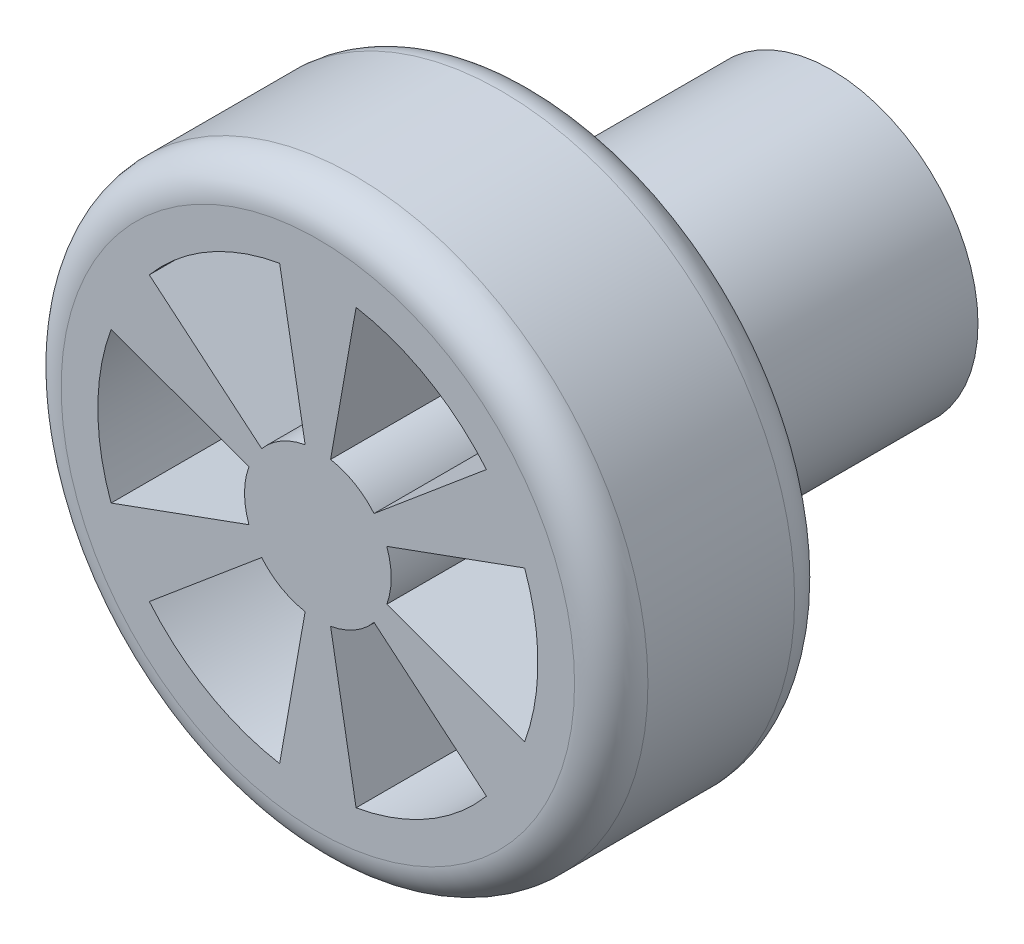
SolidWorks part; units mm, degrees
ref_plane "Front Plane" through (0, 0, 0) normal (0, 0, 1) x (1, 0, 0)
ref_plane "Top Plane" through (0, 0, 0) normal (0, 1, 0) x (1, 0, 0)
ref_plane "Right Plane" through (0, 0, 0) normal (1, 0, 0) x (0, 0, -1)
sketch "Sketch1" plane through (0, 0, 0) normal (0, 0, 1) x (1, 0, 0)
  circle A0 centre (0, 0) radius 101.6
extrude "Boss-Extrude2" add sketch "Sketch1" along normal blind 76.2
sketch "Sketch4" plane through (0, 0, 76.2) normal (0, 0, 1) x (1, 0, 0)
  circle A0 centre (0, 0) radius 25.4
sketch "Sketch5" plane through (0, 0, 0) normal (0, 0, -1) x (-1, 0, 0)
  line L0 (25.4, 0) -> (76.2, 0) construction
  line L1 (23.8682, 8.6873) -> (71.6046, 26.0619)
  line L2 (23.8682, -8.6873) -> (71.6046, -26.0619)
  line L3 (19.4575, -16.3268) -> (58.3726, -48.9804)
  line L4 (4.4107, -25.0141) -> (13.232, -75.0424)
  line L5 (-4.4107, -25.0141) -> (-13.232, -75.0424)
  line L6 (-19.4575, -16.3268) -> (-58.3726, -48.9804)
  line L7 (-23.8682, -8.6873) -> (-71.6046, -26.0619)
  line L8 (-23.8682, 8.6873) -> (-71.6046, 26.0619)
  line L9 (-19.4575, 16.3268) -> (-58.3726, 48.9804)
  line L10 (-4.4107, 25.0141) -> (-13.232, 75.0424)
  line L11 (4.4107, 25.0141) -> (13.232, 75.0424)
  line L12 (19.4575, 16.3268) -> (58.3726, 48.9804)
  arc A0 (71.6046, -26.0619) -> (71.6046, 26.0619) centre (0, 0) ccw
  arc A1 (23.8682, -8.6873) -> (23.8682, 8.6873) centre (0, 0) ccw
  arc A2 (13.232, -75.0424) -> (58.3726, -48.9804) centre (0, 0) ccw
  arc A3 (4.4107, -25.0141) -> (19.4575, -16.3268) centre (0, 0) ccw
  arc A4 (-58.3726, -48.9804) -> (-13.232, -75.0424) centre (0, 0) ccw
  arc A5 (-19.4575, -16.3268) -> (-4.4107, -25.0141) centre (0, 0) ccw
  arc A6 (-71.6046, 26.0619) -> (-71.6046, -26.0619) centre (0, 0) ccw
  arc A7 (-23.8682, 8.6873) -> (-23.8682, -8.6873) centre (0, 0) ccw
  arc A8 (-13.232, 75.0424) -> (-58.3726, 48.9804) centre (0, 0) ccw
  arc A9 (-4.4107, 25.0141) -> (-19.4575, 16.3268) centre (0, 0) ccw
  arc A10 (58.3726, 48.9804) -> (13.232, 75.0424) centre (0, 0) ccw
  arc A11 (19.4575, 16.3268) -> (4.4107, 25.0141) centre (0, 0) ccw
  point P31 (0, 0)
  dimension "D1" = 20
  dimension "D2" = 6
extrude "Cut-Extrude1" cut sketch "Sketch5" against normal up to next
fillet "Fillet1" radius 12.7 2 edges at (101.6, 0, 0) (101.6, 0, 76.2)
sketch "Sketch6" plane through (0, 0, 0) normal (0, 0, -1) x (-1, 0, 0)
  circle A0 centre (0, 0) radius 50.8
extrude "Boss-Extrude4" add sketch "Sketch6" along normal blind 101.6 separate body contours A0
